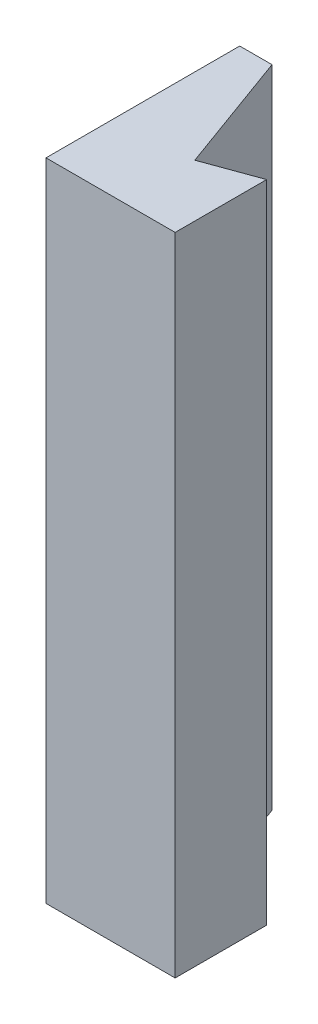
SolidWorks part; units mm, degrees
ref_plane "Front Plane" through (0, 0, 0) normal (0, 0, 1) x (1, 0, 0)
ref_plane "Top Plane" through (0, 0, 0) normal (0, 1, 0) x (1, 0, 0)
ref_plane "Right Plane" through (0, 0, 0) normal (1, 0, 0) x (0, 0, -1)
sketch "Sketch1" plane through (0, 0, 0) normal (0, 1, 0) x (1, 0, 0)
  line L0 (-6.35, 19.05) -> (2.3373, -4.8182)
  line L1 (12.7, -19.05) -> (-12.7, -19.05)
  line L2 (12.7, -19.05) -> (12.7, -1.0465)
  line L3 (-6.35, 19.05) -> (-12.7, 19.05)
  line L4 (-12.7, -19.05) -> (-12.7, 19.05)
  line L5 (12.7, -19.05) -> (-12.7, 19.05) construction
  line L6 (12.7, 19.05) -> (-12.7, -19.05) construction
  line L7 (2.3373, -4.8182) -> (12.7, -1.0465)
  point P0 (0, 0)
  dimension "D1" = 6.35
  dimension "D2" = 90
  dimension "D3" = 110
extrude "Boss-Extrude2" add sketch "Sketch1" along normal blind 127
